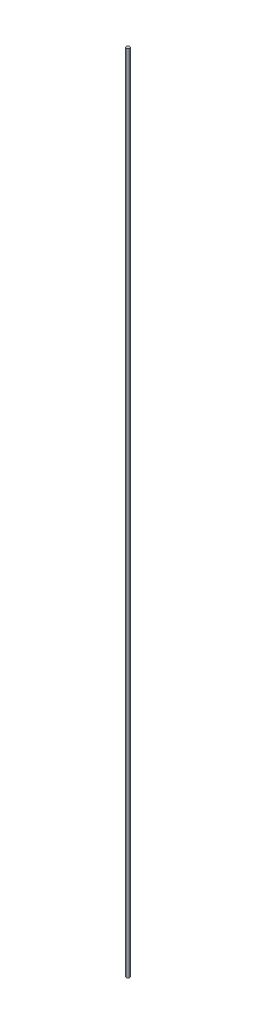
SolidWorks part; units mm, degrees
material "Copper"
ref_plane "Front Plane" through (0, 0, 0) normal (0, 0, 1) x (1, 0, 0)
ref_plane "Top Plane" through (0, 0, 0) normal (0, 1, 0) x (1, 0, 0)
ref_plane "Right Plane" through (0, 0, 0) normal (1, 0, 0) x (0, 0, -1)
sketch "Sketch1" plane through (0, 0, 0) normal (0, 1, 0) x (1, 0, 0)
  circle A0 centre (0, 0) radius 2.5
  dimension "D1" = 5
extrude "Boss-Extrude1" add sketch "Sketch1" along normal blind 1250
